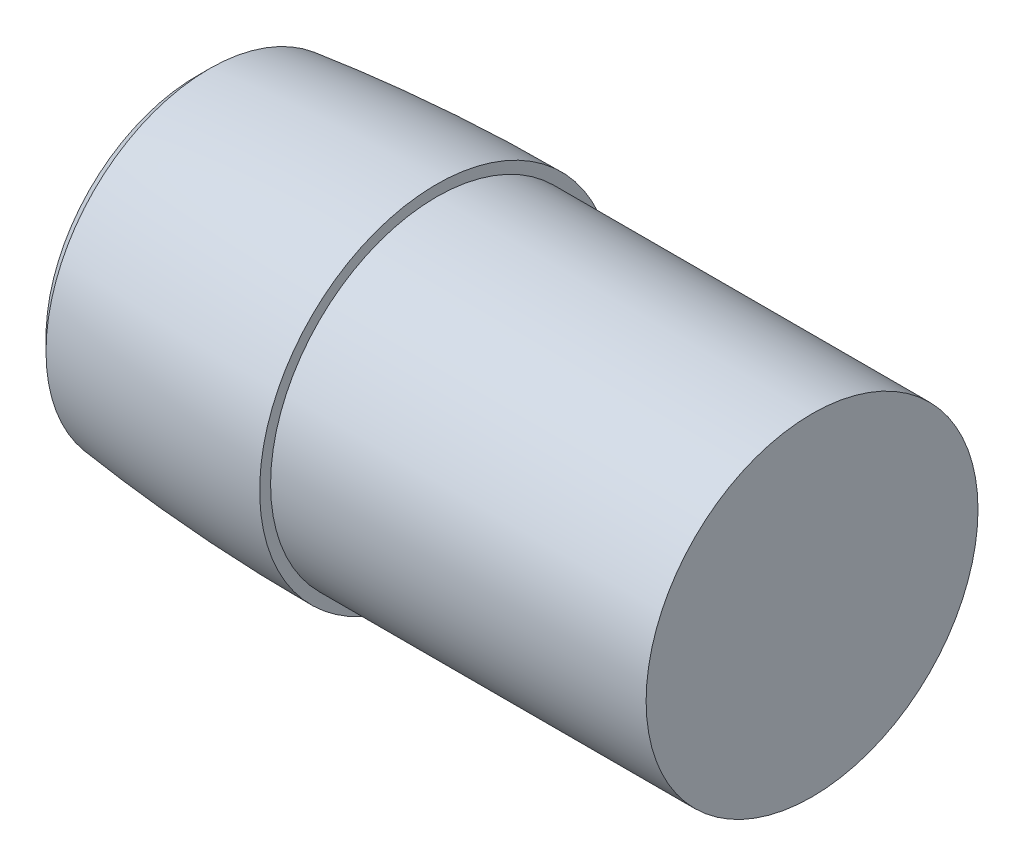
SolidWorks part; units mm, degrees
ref_plane "Front Plane" through (0, 0, 0) normal (0, 0, 1) x (1, 0, 0)
ref_plane "Top Plane" through (0, 0, 0) normal (0, 1, 0) x (1, 0, 0)
ref_plane "Right Plane" through (0, 0, 0) normal (1, 0, 0) x (0, 0, -1)
sketch "Sketch2" plane through (0, 0, 0) normal (0, 0, 1) x (1, 0, 0)
  line L0 (-0.0615, 438.7381) -> (-0.0615, 436.2381) construction
  line L1 (-0.0615, 438.7381) -> (-0.0615, 436.2381)
  line L3 (-0.0615, 436.2381) -> (85.9385, 436.2381)
  line L4 (85.9385, 436.2381) -> (85.9385, 398.2381)
  line L6 (85.9385, 398.2381) -> (80.9385, 398.2381)
  line L7 (-5.0615, 436.2381) -> (-5.0615, 431.2381)
  line L8 (-5.0615, 431.2381) -> (80.9385, 431.2381)
  line L12 (-0.0615, 403.2381) -> (-166.5183, 403.2381) construction
  line L13 (-0.0615, 398.2381) -> (-190.0615, 398.2381) construction
  line L16 (80.9385, 403.2381) -> (-0.0615, 403.2381) construction
  line L17 (85.9385, 398.2381) -> (-0.0615, 398.2381) construction
  line L18 (80.9385, 398.2381) -> (80.9385, 431.2381)
  line L19 (80.9385, 431.2381) -> (80.9385, 403.2381) construction
  line L20 (-190.0615, 398.2381) -> (-231.9833, 398.2381) construction
  line L21 (80.9385, 398.2381) -> (85.9385, 398.2381) construction
  line L23 (-52.0945, 435.6343) -> (-54.9338, 432.7951)
  line L24 (-0.0615, 441.2674) -> (-0.0615, 436.2381) construction
  line L25 (-54.9338, 432.7951) -> (-54.9338, 435.6744) construction
  arc A3 (-5.0615, 436.2381) -> (-166.5183, 403.2381) centre (0, 0) ccw construction
  arc A5 (-5.0615, 436.2381) -> (-54.9338, 432.7951) centre (0, 0) ccw
  arc A6 (80.9385, 431.2077) -> (80.7764, 431.2381) centre (0, 0) ccw
  arc A7 (-0.0615, 441.2674) -> (-190.0615, 398.2381) centre (0, 0) ccw construction
  arc A8 (-0.0615, 438.7381) -> (-52.0615, 435.6383) centre (0, 0) ccw
  arc A11 (-0.0615, 438.7381) -> (-52.0945, 435.6343) centre (0, 0) ccw construction
  arc A12 (-0.0615, 438.7381) -> (-52.0945, 435.6343) centre (0, 0) ccw
  arc A13 (80.9385, 431.2077) -> (80.7764, 431.2381) centre (0, 0) ccw construction
  arc A14 (80.9385, 431.2077) -> (80.7764, 431.2381) centre (0, 0) ccw
  dimension "D1" = 49.8722
  dimension "D10" = 38
  dimension "D3" = 86
  dimension "D4" = 2.5
  dimension "D5" = 5
  dimension "D6" = 135.1278
  dimension "D7" = 276
  dimension "D8" = 5
  dimension "D9" = 45
revolve "Revolve1" add sketch "Sketch2" angle 360 about L20
